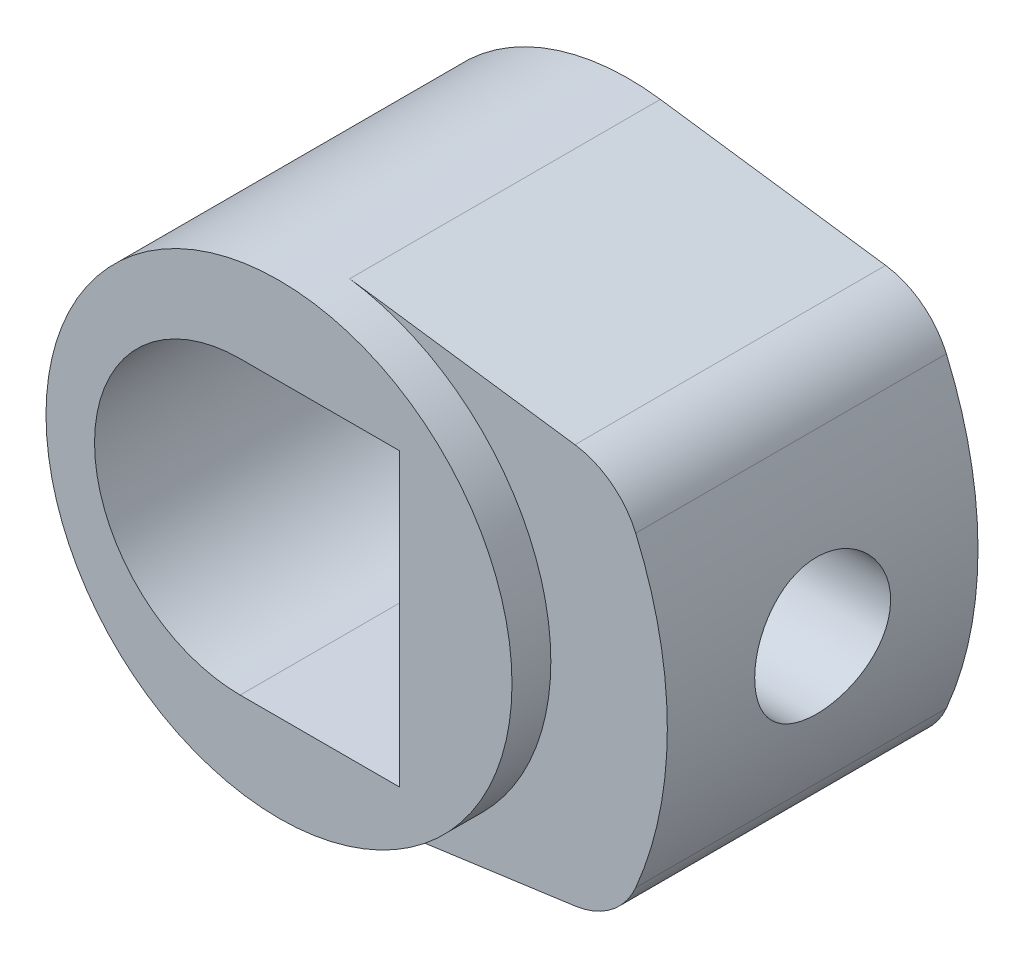
SolidWorks part; units mm, degrees
ref_plane "Ebene vorne" through (0, 0, 0) normal (0, 0, 1) x (1, 0, 0)
ref_plane "Ebene oben" through (0, 0, 0) normal (0, 1, 0) x (1, 0, 0)
ref_plane "Ebene rechts" through (0, 0, 0) normal (1, 0, 0) x (0, 0, -1)
ref_plane "Plane1" through (0, 0, -1) normal (0, 0, 1) x (1, 0, 0)
sketch "Sketch1" plane through (0, 0, -1) normal (0, 0, 1) x (1, 0, 0)
  line L0 (8.6603, 5) -> (1.82, 5.9437)
  line L1 (1.82, -5.9437) -> (8.6603, -5)
  arc A0 (1.82, 5.9437) -> (1.82, -5.9437) centre (1, 0) ccw
  arc A1 (8.6603, -5) -> (8.6603, 5) centre (0, 0) ccw
extrude "Boss-Extrude1" add sketch "Sketch1" against normal blind 8
sketch "Sketch2" plane through (0, 0, -1) normal (0, 0, 1) x (1, 0, 0)
  circle A0 centre (1, 0) radius 6
extrude "Boss-Extrude2" add sketch "Sketch2" along normal blind 1
sketch "Sketch3" plane through (0, 0, 0) normal (0, 0, 1) x (1, 0, 0)
  line L0 (0, -3.75) -> (4.1, -3.75)
  line L1 (4.1, -3.75) -> (4.1, 3.75)
  line L2 (4.1, 3.75) -> (0, 3.75)
  arc A0 (0, 3.75) -> (0, -3.75) centre (0, 0) ccw
extrude "Cut-Extrude1" cut sketch "Sketch3" against normal through all
sketch "Sketch4" plane through (4.1, 0, 0) normal (-1, 0, 0) x (0, 0, 1)
  line L0 (-9, -3) -> (-3.2679, -3)
  line L1 (-3.2679, -3) -> (-1.5359, 0)
  line L2 (-1.5359, 0) -> (-3.2679, 3)
  line L3 (-3.2679, 3) -> (-9, 3)
  line L4 (-9, 3) -> (-9, -3)
extrude "Cut-Extrude2" cut sketch "Sketch4" against normal blind 2.9
hole_wizard "HoleWzd1" positions "Sketch6" profile "Sketch5" hole size "Ø3.5" standard "ANSI Metric"
sketch "Sketch6" plane through (7, 0, 0) normal (-1, 0, 0) x (0, 0, 1)
  point P0 (-5, 0)
sketch "Sketch5" plane through (7, 0, -5) normal (0, 1, 0) x (0, 0, 1)
  line L0 (0, 0) -> (0, 3)
  line L1 (0, 3) -> (1.75, 3)
  line L2 (1.75, 3) -> (1.75, 0)
  line L5 (1.75, 0) -> (0, 0)
  line L11 (0, -6.35) -> (0, 107.95) construction
  dimension "Thru Hole Dia." = 3.5
  dimension "Thru Hole Depth" = 3
fillet "Fillet1" radius 0.6 2 edges at (4.1, 3, -6.134) (4.1, -3, -6.134)
fillet "Fillet2" radius 2 2 edges at (8.6603, -5, -5) (8.6603, 5, -5)
